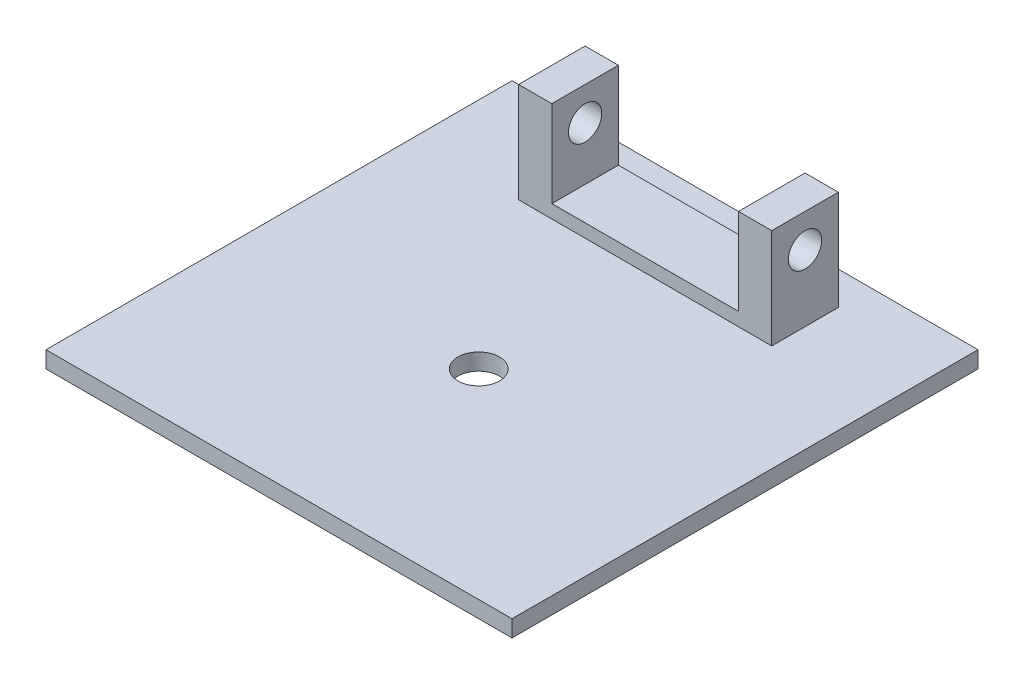
SolidWorks part; units mm, degrees
ref_plane "Front Plane" through (0, 0, 0) normal (0, 0, 1) x (1, 0, 0)
ref_plane "Top Plane" through (0, 0, 0) normal (0, 1, 0) x (1, 0, 0)
ref_plane "Right Plane" through (0, 0, 0) normal (1, 0, 0) x (0, 0, -1)
sketch "Sketch1" plane through (0, 0, 0) normal (0, 1, 0) x (1, 0, 0)
  line L1 (-88.9, -88.9) -> (88.9, -88.9)
  line L2 (-88.9, -88.9) -> (-88.9, 88.9)
  line L3 (-88.9, 88.9) -> (88.9, 88.9)
  line L4 (88.9, -88.9) -> (88.9, 88.9)
  line L5 (-88.9, -88.9) -> (88.9, 88.9) construction
  line L6 (-88.9, 88.9) -> (88.9, -88.9) construction
  point P0 (0, 0)
  dimension "D1" = 177.8
  dimension "D2" = 177.8
extrude "Boss-Extrude1" add sketch "Sketch1" along normal blind 6.35
sketch "Sketch2" plane through (0, 6.35, 0) normal (0, 1, 0) x (1, 0, 0)
  line L0 (0, 0) -> (0, -12.7) construction
  circle A0 centre (0, -12.7) radius 7.9375
  dimension "D1" = 15.875
  dimension "D2" = 12.7
extrude "Cut-Extrude1" cut sketch "Sketch2" against normal through all
sketch "Sketch3" plane through (0, 6.35, 0) normal (0, 1, 0) x (1, 0, 0)
  line L0 (0, -12.7) -> (0, 63.5) construction
  line L1 (-48.3035, 50.8) -> (48.3035, 50.8)
  line L2 (-48.3035, 50.8) -> (-48.3035, 76.2)
  line L3 (-48.3035, 76.2) -> (48.3035, 76.2)
  line L4 (48.3035, 50.8) -> (48.3035, 76.2)
  line L5 (-48.3035, 50.8) -> (48.3035, 76.2) construction
  line L6 (-48.3035, 76.2) -> (48.3035, 50.8) construction
  point P0 (0, 63.5)
  dimension "D1" = 76.2
  dimension "D2" = 25.4
extrude "Boss-Extrude2" add sketch "Sketch3" along normal blind 38.1
sketch "Sketch4" plane through (0, 0, -76.2) normal (0, 0, -1) x (-1, 0, 0)
  line L0 (-48.3035, 44.45) -> (48.3035, 44.45) construction
  line L1 (-35.6035, 44.45) -> (35.6035, 44.45)
  line L2 (-35.6035, 44.45) -> (-35.6035, 11.43)
  line L3 (-35.6035, 11.43) -> (35.6035, 11.43)
  line L4 (35.6035, 44.45) -> (35.6035, 11.43)
  line L5 (-48.3035, 44.45) -> (-48.3035, 6.35) construction
  line L6 (48.3035, 44.45) -> (48.3035, 6.35) construction
  line L7 (-88.9, 6.35) -> (88.9, 6.35) construction
  dimension "D1" = 12.7
  dimension "D2" = 12.7
  dimension "D3" = 5.08
extrude "Cut-Extrude2" cut sketch "Sketch4" against normal up to next
sketch "Sketch5" plane through (-48.3035, 0, 0) normal (-1, 0, 0) x (0, 0, 1)
  line L0 (-63.5, 6.35) -> (-63.5, 31.75) construction
  line L1 (-76.2, 6.35) -> (-50.8, 6.35) construction
  circle A0 centre (-63.5, 31.75) radius 6.35
  dimension "D1" = 12.7
  dimension "D2" = 25.4
extrude "Cut-Extrude3" cut sketch "Sketch5" against normal through all
